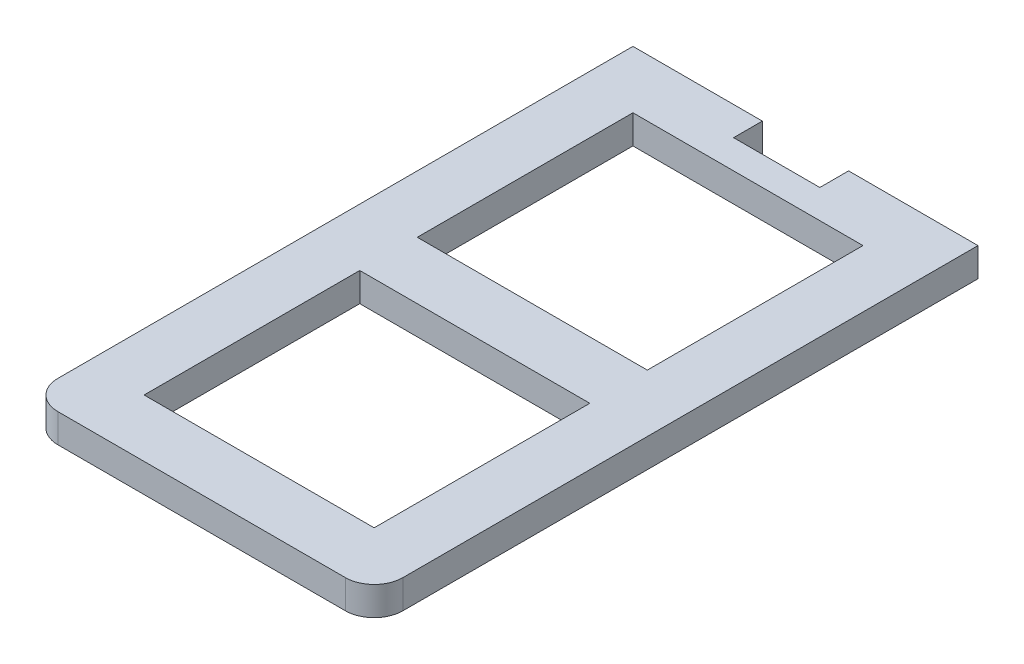
SolidWorks part; units mm, degrees
material "Perspex (TM) GS Acrylic Cast Sheet"
ref_plane "Front Plane" through (0, 0, 0) normal (0, 0, 1) x (1, 0, 0)
ref_plane "Top Plane" through (0, 0, 0) normal (0, 1, 0) x (1, 0, 0)
ref_plane "Right Plane" through (0, 0, 0) normal (1, 0, 0) x (0, 0, -1)
sketch "Sketch1" plane through (0, 0, 0) normal (0, 0, 1) x (1, 0, 0)
  line L1 (-30, -2.5) -> (30, -2.5)
  line L2 (-30, -2.5) -> (-30, 2.5)
  line L3 (-30, 2.5) -> (30, 2.5)
  line L4 (30, -2.5) -> (30, 2.5)
  line L5 (-30, -2.5) -> (30, 2.5) construction
  line L6 (-30, 2.5) -> (30, -2.5) construction
  point P0 (0, 0)
  dimension "D1" = 60
  dimension "D2" = 5
extrude "Boss-Extrude1" add sketch "Sketch1" along normal blind 105
sketch "Sketch2" plane through (0, -2.5, 0) normal (0, -1, 0) x (1, 0, 0)
  line L0 (0, 0) -> (0, 105)
  line L1 (-30, 0) -> (30, 0) construction
  line L2 (-30, 105) -> (30, 105) construction
  line L3 (-20, 52.5) -> (20, 52.5)
  line L4 (-20, 95) -> (20, 95)
  line L5 (-20, 95) -> (-20, 10)
  line L6 (-20, 10) -> (20, 10)
  line L7 (20, 95) -> (20, 10)
  line L8 (-20, 95) -> (20, 10) construction
  line L9 (-20, 10) -> (20, 95) construction
  line L11 (-20, 47.5) -> (20, 47.5)
  line L12 (-20, 47.5) -> (-20, 57.5)
  line L13 (-20, 57.5) -> (20, 57.5)
  line L14 (20, 47.5) -> (20, 57.5)
  line L15 (-20, 47.5) -> (20, 57.5) construction
  line L16 (-20, 57.5) -> (20, 47.5) construction
  point P6 (0, 52.5)
  point P13 (0, 52.5)
  dimension "D1" = 10
  dimension "D2" = 10
  dimension "D3" = 10
  dimension "D4" = 40
  dimension "D5" = 40
extrude "Cut-Extrude1" cut sketch "Sketch2" against normal blind 105 contours L12 L13 L0 L4 L5 L3 | L14 L3 L7 L4 L0 L13 | L14 L11 L0 L6 L7 L3 | L11 L12 L3 L5 L6 L0
fillet "Fillet1" radius 5 2 edges at (30, 0, 105) (-30, 0, 105)
sketch "Sketch4" plane through (0, -2.5, 0) normal (0, -1, 0) x (1, 0, 0)
  line L0 (-30, 0) -> (30, 0) construction
  line L1 (7.5, -5) -> (-7.5, -5)
  line L2 (7.5, -5) -> (7.5, 5)
  line L3 (7.5, 5) -> (-7.5, 5)
  line L4 (-7.5, -5) -> (-7.5, 5)
  line L5 (7.5, -5) -> (-7.5, 5) construction
  line L6 (7.5, 5) -> (-7.5, -5) construction
  point P0 (0, 0)
  dimension "D1" = 10
  dimension "D2" = 15
extrude "Cut-Extrude3" cut sketch "Sketch4" against normal blind 10
